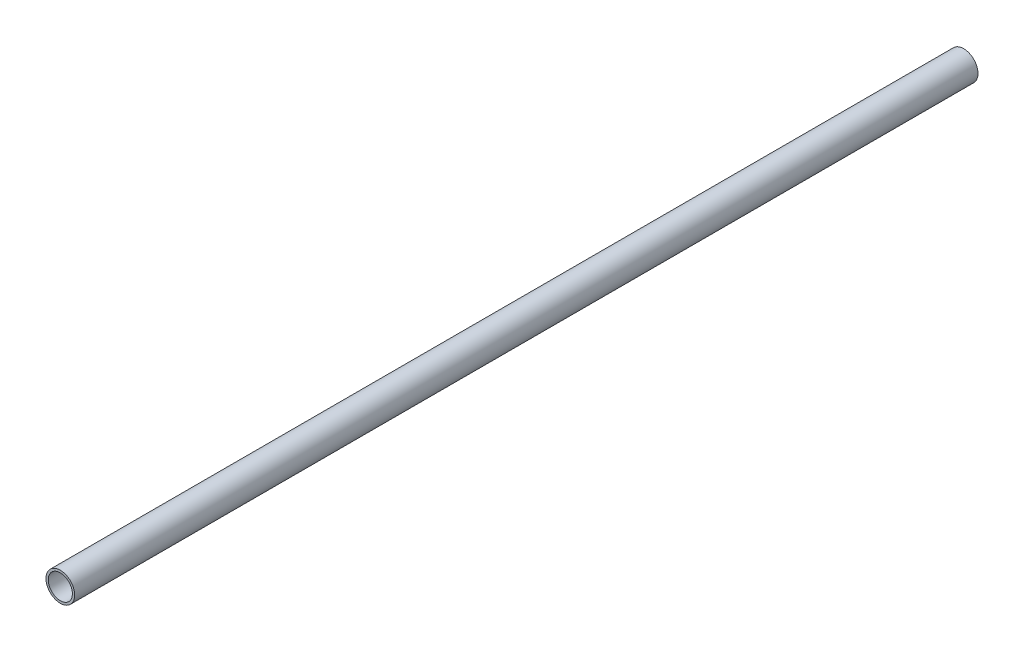
SolidWorks part; units mm, degrees
material "AISI 316 Stainless Steel Sheet (SS)"
ref_plane "Front Plane" through (0, 0, 0) normal (0, 0, 1) x (1, 0, 0)
ref_plane "Top Plane" through (0, 0, 0) normal (0, 1, 0) x (1, 0, 0)
ref_plane "Right Plane" through (0, 0, 0) normal (1, 0, 0) x (0, 0, -1)
sketch "Sketch1" plane through (0, 0, 0) normal (0, 0, 1) x (1, 0, 0)
  circle A0 centre (0, 0) radius 6.35
  circle A1 centre (0, 0) radius 5.35
  dimension "D1" = 12.7
  dimension "D2" = 10.7
extrude "Boss-Extrude1" add sketch "Sketch1" along normal blind 400
